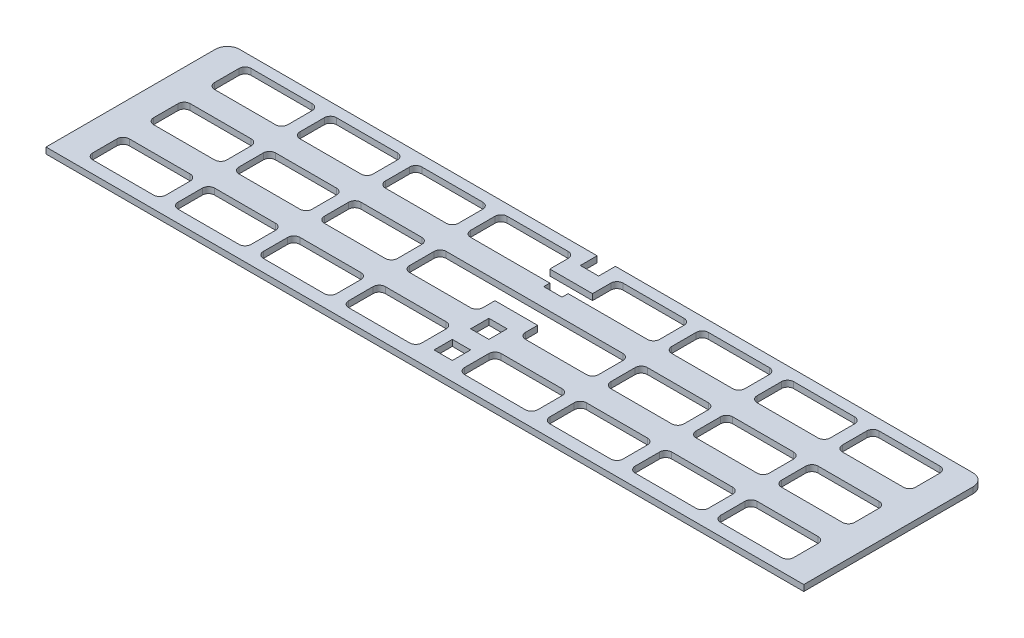
SolidWorks part; units mm, degrees
material "Balsa"
ref_plane "Front Plane" through (0, 0, 0) normal (0, 0, 1) x (1, 0, 0)
ref_plane "Top Plane" through (0, 0, 0) normal (0, 1, 0) x (1, 0, 0)
ref_plane "Right Plane" through (0, 0, 0) normal (1, 0, 0) x (0, 0, -1)
sketch "Sketch1" plane through (0, 0, 0) normal (0, 1, 0) x (1, 0, 0)
  line L0 (0, 0) -> (385.191, 0)
  line L1 (372.491, 188.976) -> (0, 188.976)
  line L2 (0, 188.976) -> (0, 0)
  line L3 (385.191, 0) -> (385.191, 176.276)
  arc A0 (372.491, 188.976) -> (385.191, 176.276) centre (372.491, 176.276) cw
  point P7 (385.191, 188.976)
  dimension "D4" = 12.7
  dimension "D1" = 188.976
  dimension "D2" = 385.191
  dimension "D3" = 188.976
extrude "Boss-Extrude1" add sketch "Sketch1" along normal blind 6.35
sketch "Sketch2" plane through (0, 6.35, 0) normal (0, 1, 0) x (1, 0, 0)
  line L0 (0, 188.976) -> (0, 0) construction
  line L9 (0, 0) -> (385.191, 0) construction
  line L68 (279.4, 19.05) -> (279.4, 44.45)
  line L69 (285.75, 12.7) -> (349.25, 12.7)
  line L70 (355.6, 19.05) -> (355.6, 44.45)
  line L71 (285.75, 50.8) -> (349.25, 50.8)
  line L72 (279.4, 82.55) -> (279.4, 107.95)
  line L73 (285.75, 76.2) -> (349.25, 76.2)
  line L74 (355.6, 82.55) -> (355.6, 107.95)
  line L76 (101.6, 19.05) -> (101.6, 44.45)
  line L77 (285.75, 114.3) -> (349.25, 114.3)
  line L78 (279.4, 146.05) -> (279.4, 171.45)
  line L79 (285.75, 139.7) -> (349.25, 139.7)
  line L80 (355.6, 146.05) -> (355.6, 171.45)
  line L81 (285.75, 177.8) -> (349.25, 177.8)
  line L91 (19.05, 12.7) -> (82.55, 12.7)
  line L92 (12.7, 19.05) -> (12.7, 44.45)
  line L93 (19.05, 50.8) -> (82.55, 50.8)
  line L94 (88.9, 19.05) -> (88.9, 44.45)
  line L95 (107.95, 12.7) -> (171.45, 12.7)
  line L96 (177.8, 19.05) -> (177.8, 44.45)
  line L97 (107.95, 50.8) -> (171.45, 50.8)
  line L98 (190.5, 19.05) -> (190.5, 44.45)
  line L99 (196.85, 12.7) -> (260.35, 12.7)
  line L100 (266.7, 19.05) -> (266.7, 44.45)
  line L101 (196.85, 50.8) -> (260.35, 50.8)
  line L102 (101.6, 82.55) -> (101.6, 107.95)
  line L103 (107.95, 76.2) -> (171.45, 76.2)
  line L104 (177.8, 82.55) -> (177.8, 107.95)
  line L105 (107.95, 114.3) -> (171.45, 114.3)
  line L106 (190.5, 82.55) -> (190.5, 107.95)
  line L107 (196.85, 76.2) -> (260.35, 76.2)
  line L108 (266.7, 82.55) -> (266.7, 107.95)
  line L109 (196.85, 114.3) -> (260.35, 114.3)
  line L110 (101.6, 146.05) -> (101.6, 171.45)
  line L111 (107.95, 139.7) -> (171.45, 139.7)
  line L112 (177.8, 146.05) -> (177.8, 171.45)
  line L113 (107.95, 177.8) -> (171.45, 177.8)
  line L114 (190.5, 146.05) -> (190.5, 171.45)
  line L115 (196.85, 139.7) -> (260.35, 139.7)
  line L116 (266.7, 146.05) -> (266.7, 171.45)
  line L117 (196.85, 177.8) -> (260.35, 177.8)
  line L118 (12.7, 82.55) -> (12.7, 107.95)
  line L119 (19.05, 76.2) -> (82.55, 76.2)
  line L120 (88.9, 82.55) -> (88.9, 107.95)
  line L121 (19.05, 114.3) -> (82.55, 114.3)
  line L122 (12.7, 146.05) -> (12.7, 171.45)
  line L123 (19.05, 139.7) -> (82.55, 139.7)
  line L124 (88.9, 146.05) -> (88.9, 171.45)
  line L125 (19.05, 177.8) -> (82.55, 177.8)
  line L126 (12.7, 19.05) -> (12.7, 82.55) construction
  arc A0 (82.55, 12.7) -> (88.9, 19.05) centre (82.55, 19.05) ccw
  arc A1 (19.05, 12.7) -> (12.7, 19.05) centre (19.05, 19.05) cw
  arc A2 (12.7, 44.45) -> (19.05, 50.8) centre (19.05, 44.45) cw
  arc A3 (82.55, 50.8) -> (88.9, 44.45) centre (82.55, 44.45) cw
  arc A4 (101.6, 44.45) -> (107.95, 50.8) centre (107.95, 44.45) cw
  arc A5 (107.95, 12.7) -> (101.6, 19.05) centre (107.95, 19.05) cw
  arc A6 (171.45, 12.7) -> (177.8, 19.05) centre (171.45, 19.05) ccw
  arc A7 (171.45, 50.8) -> (177.8, 44.45) centre (171.45, 44.45) cw
  arc A8 (190.5, 44.45) -> (196.85, 50.8) centre (196.85, 44.45) cw
  arc A9 (196.85, 12.7) -> (190.5, 19.05) centre (196.85, 19.05) cw
  arc A10 (260.35, 12.7) -> (266.7, 19.05) centre (260.35, 19.05) ccw
  arc A11 (260.35, 50.8) -> (266.7, 44.45) centre (260.35, 44.45) cw
  arc A12 (101.6, 107.95) -> (107.95, 114.3) centre (107.95, 107.95) cw
  arc A13 (107.95, 76.2) -> (101.6, 82.55) centre (107.95, 82.55) cw
  arc A14 (171.45, 76.2) -> (177.8, 82.55) centre (171.45, 82.55) ccw
  arc A15 (171.45, 114.3) -> (177.8, 107.95) centre (171.45, 107.95) cw
  arc A16 (190.5, 107.95) -> (196.85, 114.3) centre (196.85, 107.95) cw
  arc A17 (196.85, 76.2) -> (190.5, 82.55) centre (196.85, 82.55) cw
  arc A18 (260.35, 76.2) -> (266.7, 82.55) centre (260.35, 82.55) ccw
  arc A19 (260.35, 114.3) -> (266.7, 107.95) centre (260.35, 107.95) cw
  arc A20 (101.6, 171.45) -> (107.95, 177.8) centre (107.95, 171.45) cw
  arc A21 (107.95, 139.7) -> (101.6, 146.05) centre (107.95, 146.05) cw
  arc A22 (171.45, 139.7) -> (177.8, 146.05) centre (171.45, 146.05) ccw
  arc A23 (171.45, 177.8) -> (177.8, 171.45) centre (171.45, 171.45) cw
  arc A24 (190.5, 171.45) -> (196.85, 177.8) centre (196.85, 171.45) cw
  arc A25 (196.85, 139.7) -> (190.5, 146.05) centre (196.85, 146.05) cw
  arc A26 (260.35, 139.7) -> (266.7, 146.05) centre (260.35, 146.05) ccw
  arc A27 (260.35, 177.8) -> (266.7, 171.45) centre (260.35, 171.45) cw
  arc A28 (12.7, 107.95) -> (19.05, 114.3) centre (19.05, 107.95) cw
  arc A29 (19.05, 76.2) -> (12.7, 82.55) centre (19.05, 82.55) cw
  arc A30 (82.55, 76.2) -> (88.9, 82.55) centre (82.55, 82.55) ccw
  arc A31 (82.55, 114.3) -> (88.9, 107.95) centre (82.55, 107.95) cw
  arc A32 (12.7, 171.45) -> (19.05, 177.8) centre (19.05, 171.45) cw
  arc A33 (19.05, 139.7) -> (12.7, 146.05) centre (19.05, 146.05) cw
  arc A34 (82.55, 139.7) -> (88.9, 146.05) centre (82.55, 146.05) ccw
  arc A35 (82.55, 177.8) -> (88.9, 171.45) centre (82.55, 171.45) cw
  arc A36 (279.4, 44.45) -> (285.75, 50.8) centre (285.75, 44.45) cw
  arc A37 (285.75, 12.7) -> (279.4, 19.05) centre (285.75, 19.05) cw
  arc A38 (349.25, 12.7) -> (355.6, 19.05) centre (349.25, 19.05) ccw
  arc A39 (349.25, 50.8) -> (355.6, 44.45) centre (349.25, 44.45) cw
  arc A40 (279.4, 107.95) -> (285.75, 114.3) centre (285.75, 107.95) cw
  arc A41 (285.75, 76.2) -> (279.4, 82.55) centre (285.75, 82.55) cw
  arc A42 (349.25, 76.2) -> (355.6, 82.55) centre (349.25, 82.55) ccw
  arc A43 (349.25, 114.3) -> (355.6, 107.95) centre (349.25, 107.95) cw
  arc A44 (279.4, 171.45) -> (285.75, 177.8) centre (285.75, 171.45) cw
  arc A45 (285.75, 139.7) -> (279.4, 146.05) centre (285.75, 146.05) cw
  arc A46 (349.25, 139.7) -> (355.6, 146.05) centre (349.25, 146.05) ccw
  arc A47 (349.25, 177.8) -> (355.6, 171.45) centre (349.25, 171.45) cw
  point P10 (88.9, 12.7)
  point P13 (12.7, 12.7)
  point P16 (12.7, 50.8)
  point P19 (101.6, 31.75)
  dimension "D7" = 3
  dimension "D5" = 6.35
  dimension "D1" = 12.7
  dimension "D2" = 76.2
  dimension "D3" = 12.7
  dimension "D4" = 38.1
  dimension "D8" = 63.5
  dimension "D9" = 25.4
  dimension "D10" = 12.7
  dimension "D6" = 4
extrude "Cut-Extrude1" cut sketch "Sketch2" against normal up to surface (6.35 mm away) up to face at (229.1007, 0, -111.3717)
sketch "Sketch3" plane through (0, 6.35, 0) normal (0, 1, 0) x (1, 0, 0)
  line L2 (0, 19.05) -> (0, 38.1)
  line L3 (0, 0) -> (-19.05, 0)
  line L4 (0, 0) -> (0, 19.05)
  line L5 (0, 19.05) -> (-19.05, 19.05)
  line L6 (-19.05, 0) -> (-19.05, 19.05)
  line L7 (0, 19.05) -> (-19.05, 19.05)
  line L8 (-19.05, 19.05) -> (-19.05, 38.1)
  line L9 (0, 38.1) -> (-19.05, 38.1)
  line L10 (0, 38.1) -> (0, 57.15)
  line L11 (0, 38.1) -> (-19.05, 38.1)
  line L12 (-19.05, 38.1) -> (-19.05, 57.15)
  line L13 (0, 57.15) -> (-19.05, 57.15)
  line L14 (0, 57.15) -> (0, 76.2)
  line L15 (0, 57.15) -> (-19.05, 57.15)
  line L16 (-19.05, 57.15) -> (-19.05, 76.2)
  line L17 (0, 76.2) -> (-19.05, 76.2)
  line L18 (0, 76.2) -> (0, 95.25)
  line L19 (0, 76.2) -> (-19.05, 76.2)
  line L20 (-19.05, 76.2) -> (-19.05, 95.25)
  line L21 (0, 95.25) -> (-19.05, 95.25)
  line L22 (0, 95.25) -> (0, 114.3)
  line L23 (0, 95.25) -> (-19.05, 95.25)
  line L24 (-19.05, 95.25) -> (-19.05, 114.3)
  line L25 (0, 114.3) -> (-19.05, 114.3)
  line L26 (0, 114.3) -> (0, 133.35)
  line L27 (0, 114.3) -> (-19.05, 114.3)
  line L28 (-19.05, 114.3) -> (-19.05, 133.35)
  line L29 (0, 133.35) -> (-19.05, 133.35)
  line L30 (0, 133.35) -> (0, 152.4)
  line L31 (0, 133.35) -> (-19.05, 133.35)
  line L32 (-19.05, 133.35) -> (-19.05, 152.4)
  line L33 (0, 152.4) -> (-19.05, 152.4)
  line L34 (0, 152.4) -> (0, 171.45)
  line L35 (0, 152.4) -> (-19.05, 152.4)
  line L36 (-19.05, 152.4) -> (-19.05, 171.45)
  line L37 (0, 171.45) -> (-19.05, 171.45)
  line L38 (0, 171.45) -> (0, 190.5)
  line L39 (0, 171.45) -> (-19.05, 171.45)
  line L40 (-19.05, 171.45) -> (-19.05, 190.5)
  line L41 (0, 190.5) -> (-19.05, 190.5)
  line L43 (0, 190.5) -> (-19.05, 190.5)
  line L74 (0, 190.5) -> (0, 209.55) [skipped]
  line L75 (-19.05, 190.5) -> (-19.05, 209.55) [skipped]
  line L76 (0, 209.55) -> (-19.05, 209.55) [skipped]
  line L77 (0, 209.55) -> (0, 228.6) [skipped]
  line L78 (0, 209.55) -> (-19.05, 209.55) [skipped]
  line L79 (-19.05, 209.55) -> (-19.05, 228.6) [skipped]
  line L80 (0, 228.6) -> (-19.05, 228.6) [skipped]
  line L81 (0, 228.6) -> (0, 247.65) [skipped]
  line L82 (0, 228.6) -> (-19.05, 228.6) [skipped]
  line L83 (-19.05, 228.6) -> (-19.05, 247.65) [skipped]
  line L84 (0, 247.65) -> (0, 266.7) [skipped]
  line L85 (0, 247.65) -> (-19.05, 247.65) [skipped]
  line L86 (-19.05, 247.65) -> (-19.05, 266.7) [skipped]
  line L87 (0, 266.7) -> (-19.05, 266.7) [skipped]
  line L88 (0, 266.7) -> (0, 285.75) [skipped]
  line L89 (0, 266.7) -> (-19.05, 266.7) [skipped]
  line L90 (-19.05, 266.7) -> (-19.05, 285.75) [skipped]
  line L91 (0, 285.75) -> (-19.05, 285.75) [skipped]
  line L92 (0, 285.75) -> (0, 304.8) [skipped]
  line L93 (0, 285.75) -> (-19.05, 285.75) [skipped]
  line L94 (-19.05, 285.75) -> (-19.05, 304.8) [skipped]
  line L95 (0, 304.8) -> (-19.05, 304.8) [skipped]
  line L96 (0, 304.8) -> (0, 323.85) [skipped]
  line L97 (0, 304.8) -> (-19.05, 304.8) [skipped]
  line L98 (-19.05, 304.8) -> (-19.05, 323.85) [skipped]
  line L99 (0, 323.85) -> (-19.05, 323.85) [skipped]
  line L100 (0, 323.85) -> (0, 342.9) [skipped]
  line L101 (0, 323.85) -> (-19.05, 323.85) [skipped]
  line L102 (-19.05, 323.85) -> (-19.05, 342.9) [skipped]
  line L103 (0, 342.9) -> (-19.05, 342.9) [skipped]
  line L104 (0, 247.65) -> (-19.05, 247.65) [skipped]
  dimension "D2" = 19.05
  dimension "D3" = 19.05
  dimension "D4" = 18
extrude "Boss-Extrude2" add sketch "Sketch3" against normal up to surface (6.35 mm away) up to face at (317.5, 0, -31.75)
ref_plane "Plane1" through (-9.525, 0, 0) normal (-1, 0, 0) x (0, 0, 1)
mirror "Mirror3" about plane through (-9.525, 0, 0) normal (-1, 0, 0) of "Boss-Extrude1"
mirror "Mirror2" about plane through (-9.525, 0, 0) normal (-1, 0, 0) of "Cut-Extrude1"
sketch "Sketch4" plane through (0, 6.35, 0) normal (0, 1, 0) x (1, 0, 0)
  line L0 (-19.05, 152.4) -> (-31.75, 152.4)
  line L1 (-31.75, 171.45) -> (-31.75, 146.05) construction
  line L2 (-38.1, 139.7) -> (-19.05, 139.7)
  line L3 (-19.05, 152.4) -> (-19.05, 133.35) construction
  line L4 (-19.05, 139.7) -> (-19.05, 152.4)
  line L5 (-38.1, 139.7) -> (-31.75, 152.4)
  line L6 (0, 152.4) -> (12.7, 152.4)
  line L7 (12.7, 171.45) -> (12.7, 146.05) construction
  line L8 (19.05, 139.7) -> (0, 139.7)
  line L9 (0, 152.4) -> (0, 133.35) construction
  line L10 (0, 139.7) -> (0, 152.4)
  line L11 (12.7, 152.4) -> (19.05, 139.7)
  line L14 (-19.05, 95.25) -> (-31.75, 95.25)
  line L15 (-31.75, 107.95) -> (-31.75, 82.55) construction
  line L17 (-19.05, 114.3) -> (-19.05, 95.25)
  line L18 (0, 114.3) -> (19.05, 114.3)
  line L19 (0, 95.25) -> (12.7, 95.25)
  line L20 (0, 114.3) -> (0, 95.25) construction
  line L21 (12.7, 107.95) -> (12.7, 82.55) construction
  line L22 (12.7, 95.25) -> (19.05, 114.3)
  line L23 (0, 95.25) -> (0, 114.3)
  line L24 (-19.05, 114.3) -> (-38.1, 114.3)
  line L25 (-38.1, 114.3) -> (-31.75, 95.25)
extrude "Cut-Extrude2" cut sketch "Sketch4" against normal through all
equation "\"D3@Sketch1\"=\"D1@Sketch1\""
